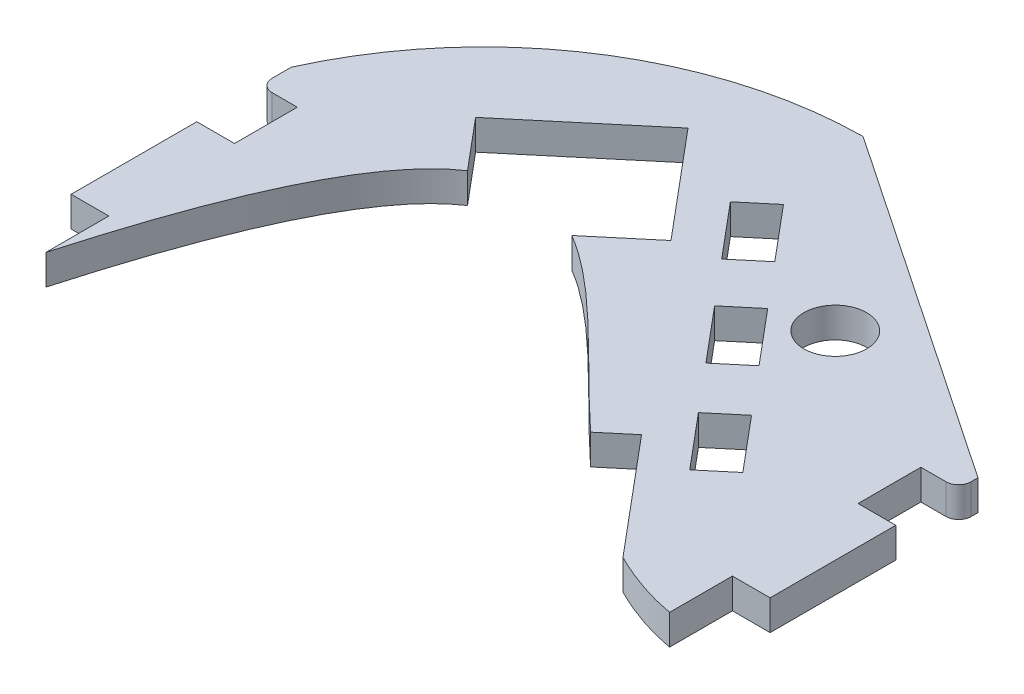
SolidWorks part; units mm, degrees
ref_plane "Alzado" through (0, 0, 0) normal (0, 0, 1) x (1, 0, 0)
ref_plane "Planta" through (0, 0, 0) normal (0, 1, 0) x (1, 0, 0)
ref_plane "Vista lateral" through (0, 0, 0) normal (1, 0, 0) x (0, 0, -1)
sketch "Croquis1" plane through (0, 0, 0) normal (0, 1, 0) x (1, 0, 0)
  circle A0 centre (0, 0) radius 30.5
extrude "Saliente-Extruir1" add sketch "Croquis1" along normal blind 2.4
sketch "Croquis2" plane through (0, 2.4, 0) normal (0, 1, 0) x (1, 0, 0)
  circle A0 centre (0, 0) radius 2
extrude "Cortar-Extruir1" cut sketch "Croquis2" against normal blind 4
sketch "Croquis5" plane through (0, 2.4, 0) normal (0, 1, 0) x (1, 0, 0)
  line L0 (0, 0) -> (0, 10)
  line L1 (28.8141, -5) -> (30.0874, -5)
  line L2 (28.8141, 5) -> (30.0874, 5)
  line L3 (-24.8141, 10) -> (-28.8141, 10)
  line L4 (24.8141, -5) -> (24.8141, -10)
  line L5 (-24.8141, -10) -> (-28.8141, -10)
  line L6 (24.8141, -5) -> (28.8141, -5)
  line L7 (24.8141, 5) -> (24.8141, 10)
  line L8 (-24.8141, 5) -> (-28.8141, 5)
  line L9 (-24.8141, 5) -> (-24.8141, 10)
  line L10 (-24.8141, -5) -> (-28.8141, -5)
  line L11 (-24.8141, -5) -> (-24.8141, -10)
  line L12 (24.8141, 5) -> (28.8141, 5)
  line L13 (24.8141, -10) -> (28.8141, -10)
  line L14 (24.8141, 10) -> (28.8141, 10)
  line L15 (-28.8141, 5) -> (-30.0874, 5)
  line L16 (-28.8141, -5) -> (-30.0874, -5)
  circle A1 centre (0, 0) radius 30.5 construction
  arc A2 (-28.8141, 10) -> (-30.0874, 5) centre (0, 0) ccw
  arc A3 (28.8141, 10) -> (28.8141, -10) centre (0, 0) cw
  arc A4 (-30.0874, -5) -> (-28.8141, -10) centre (0, 0) ccw
  arc A5 (30.0874, -5) -> (28.8141, -10) centre (0, 0) cw
  arc A6 (28.8141, 10) -> (30.0874, 5) centre (0, 0) cw
extrude "Cortar-Extruir3" cut sketch "Croquis5" against normal blind 4
sketch "Croquis7" plane through (0, 2.4, 0) normal (0, 1, 0) x (1, 0, 0)
  line L0 (-8.1011, 29.1011) -> (9.5756, 8.0348)
  line L1 (-1.4002, 16.4481) -> (-0.7574, 15.682)
  line L2 (-8.1011, 29.1011) -> (-27.2522, 13.0314)
  line L3 (27.2522, -13.0314) -> (8.1011, -29.1011)
  line L4 (8.1011, -29.1011) -> (-27.2522, 13.0314)
  line L5 (1.4284, 22.4114) -> (-0.8697, 20.4831)
  line L6 (1.4284, 22.4114) -> (4.6423, 18.5812)
  line L7 (4.6423, 18.5812) -> (2.3442, 16.6528)
  line L8 (2.3442, 16.6528) -> (-0.8697, 20.4831)
  line L9 (-24.8141, -10) -> (-28.8141, -10)
  line L10 (24.8141, -10) -> (28.8141, -10)
  line L11 (9.5756, 8.0348) -> (18.4139, -2.4983)
  line L12 (18.4139, -2.4983) -> (27.2522, -13.0314)
  line L13 (11.4555, 1.1272) -> (19.169, -8.0653)
  line L14 (19.169, -8.0653) -> (9.9765, -15.7788)
  line L15 (9.9765, -15.7788) -> (2.263, -6.5863)
  line L16 (11.4555, 1.1272) -> (2.263, -6.5863)
  line L17 (-1.4002, 16.4481) -> (-7.8281, 24.1085)
  line L18 (-1.4002, 16.4481) -> (-10.5927, 8.7346)
  line L19 (-10.5927, 8.7346) -> (-17.0206, 16.3951)
  line L20 (-7.8281, 24.1085) -> (-17.0206, 16.3951)
  line L21 (16.2929, 4.6967) -> (14.6859, 6.6118)
  line L22 (16.2929, 4.6967) -> (17.8998, 2.7815)
  line L23 (14.6859, 6.6118) -> (12.3878, 4.6834)
  line L24 (17.8998, 2.7815) -> (15.6017, 0.8532)
  line L25 (15.6017, 0.8532) -> (12.3878, 4.6834)
  line L26 (-0.7574, 15.682) -> (-5.0494, 12.0807)
  arc A1 (-28.8141, -10) -> (28.8141, -10) centre (0, 0) ccw
  spline S0 degree 3 poles (24.8141, -10) (2.6081, -6.0995) (-10.3265, 41.1093) (-24.8141, -10) knots 0 0 0 0 1 1 1 1
  point P7 (-9.5756, -8.0348)
extrude "Cortar-Extruir5" cut sketch "Croquis7" against normal blind 4
sketch "Croquis9" plane through (0, 2.4, 0) normal (0, 1, 0) x (1, 0, 0)
  line L0 (-8.3073, 29.3469) -> (22.8679, -7.8063)
  line L2 (7.9714, 14.6138) -> (11.1854, 10.7835)
  line L3 (-8.3073, 29.3469) -> (-21.7131, 18.0981)
  line L4 (-21.7131, 18.0981) -> (9.4621, -19.0551)
  line L5 (9.4621, -19.0551) -> (22.8679, -7.8063)
  line L6 (11.1854, 10.7835) -> (8.8872, 8.8552)
  line L7 (7.9714, 14.6138) -> (5.6733, 12.6854)
  arc A1 (28.8141, 10) -> (-28.8141, 10) centre (0, 0) ccw construction
extrude "Cortar-Extruir6" cut sketch "Croquis9" against normal blind 10 contours L2 L7 L0 L6
sketch "Croquis10" plane through (0, 2.4, 0) normal (0, 1, 0) x (1, 0, 0)
  line L0 (0, 0) -> (12, 0)
  line L1 (12, 0) -> (12, 16)
  circle A0 centre (12, 16) radius 2.5
extrude "Cortar-Extruir7" cut sketch "Croquis10" against normal blind 3
sketch "Croquis11" plane through (0, 2.4, 0) normal (0, 1, 0) x (1, 0, 0)
  line L0 (-24.8141, 10) -> (-27.8141, 10)
  line L1 (-24.8141, 10) -> (-28.8141, 10) construction
  line L2 (-27.8141, 10) -> (-27.8141, 12.5151)
  line L3 (-24.8141, 5) -> (-27.8141, 5)
  line L4 (-24.8141, 5) -> (-30.0874, 5) construction
  line L5 (-27.8141, 5) -> (-27.8141, -5)
  line L6 (-24.8141, -5) -> (-30.0874, -5) construction
  line L7 (24.8141, 10) -> (27.8141, 10)
  line L8 (24.8141, 10) -> (28.8141, 10) construction
  line L9 (27.8141, 10) -> (27.8141, 12.5151)
  line L10 (24.8141, 5) -> (27.8141, 5)
  line L11 (24.8141, 5) -> (30.0874, 5) construction
  line L12 (27.8141, 5) -> (27.8141, -5)
  line L13 (24.8141, -5) -> (30.0874, -5) construction
  arc A0 (28.8141, 10) -> (-28.8141, 10) centre (0, 0) ccw construction
  line M20 (24.8141, -5) -> (30.0874, -5)
  arc M21 (30.0874, -5) -> (30.0874, 5) centre (0, 0) ccw
  line M22 (30.0874, 5) -> (24.8141, 5)
  line M24 (24.8141, 10) -> (28.8141, 10)
  arc M25 (28.8141, 10) -> (-28.8141, 10) centre (0, 0) ccw
  line M26 (-28.8141, 10) -> (-24.8141, 10)
  line M28 (-24.8141, 5) -> (-30.0874, 5)
  arc M29 (-30.0874, 5) -> (-30.0874, -5) centre (0, 0) ccw
  line M30 (-30.0874, -5) -> (-24.8141, -5)
extrude "Cortar-Extruir8" cut sketch "Croquis11" against normal through all and the other way through all contours L12 M22 M20 M21 | L9 M24 M25 | L5 M28 M29 M30 | L2 M26 M25
sketch "Croquis12" plane through (0, 2.4, 0) normal (0, 1, 0) x (1, 0, 0)
  line L3 (29.8013, 10.2046) -> (-1.7022, 31.454)
  circle A0 centre (0, 0) radius 31.5
  line M23 (27.8141, 10) -> (27.8141, 12.5151)
  arc M24 (27.8141, 12.5151) -> (-27.8141, 12.5151) centre (0, 0) ccw
extrude "Cortar-Extruir9" cut sketch "Croquis12" against normal blind 10 contours L3 M23 M24
fillet "Redondeo1" radius 1 2 edges at (27.8141, 1.2, -10) (-27.8141, 1.2, -10)
sketch "Croquis13" plane through (0, 2.4, 0) normal (0, 1, 0) x (1, 0, 0)
  line L0 (1.4284, 22.4114) -> (-0.8697, 20.4831)
  line L1 (1.4284, 22.4114) -> (1.2356, 22.6412)
  line L2 (-0.8697, 20.4831) -> (-1.0626, 20.7129)
  line L3 (1.2356, 22.6412) -> (-1.0626, 20.7129)
  line L4 (2.3442, 16.6528) -> (4.6423, 18.5812)
  line L5 (2.3442, 16.6528) -> (2.537, 16.423)
  line L6 (4.6423, 18.5812) -> (4.8352, 18.3514)
  line L7 (2.537, 16.423) -> (4.8352, 18.3514)
  line L8 (7.9714, 14.6138) -> (5.6733, 12.6854)
  line L9 (7.9714, 14.6138) -> (7.7786, 14.8436)
  line L10 (5.6733, 12.6854) -> (5.4804, 12.9152)
  line L11 (7.7786, 14.8436) -> (5.4804, 12.9152)
  line L12 (7.9714, 14.6138) -> (5.6733, 12.6854) construction
  line L13 (7.9714, 14.6138) -> (11.1854, 10.7835) construction
  line L14 (8.8872, 8.8552) -> (11.1854, 10.7835)
  line L15 (8.8872, 8.8552) -> (9.0801, 8.6254)
  line L16 (11.1854, 10.7835) -> (11.3782, 10.5537)
  line L17 (9.0801, 8.6254) -> (11.3782, 10.5537)
  line L18 (14.6859, 6.6118) -> (12.3878, 4.6834)
  line L19 (14.6859, 6.6118) -> (14.493, 6.8416)
  line L20 (12.3878, 4.6834) -> (12.1949, 4.9132)
  line L21 (14.493, 6.8416) -> (12.1949, 4.9132)
  line L22 (17.8998, 2.7815) -> (15.6017, 0.8532)
  line L23 (17.8998, 2.7815) -> (18.0927, 2.5517)
  line L24 (15.6017, 0.8532) -> (15.7945, 0.6234)
  line L25 (18.0927, 2.5517) -> (15.7945, 0.6234)
extrude "Cortar-Extruir10" cut sketch "Croquis13" against normal blind 3
